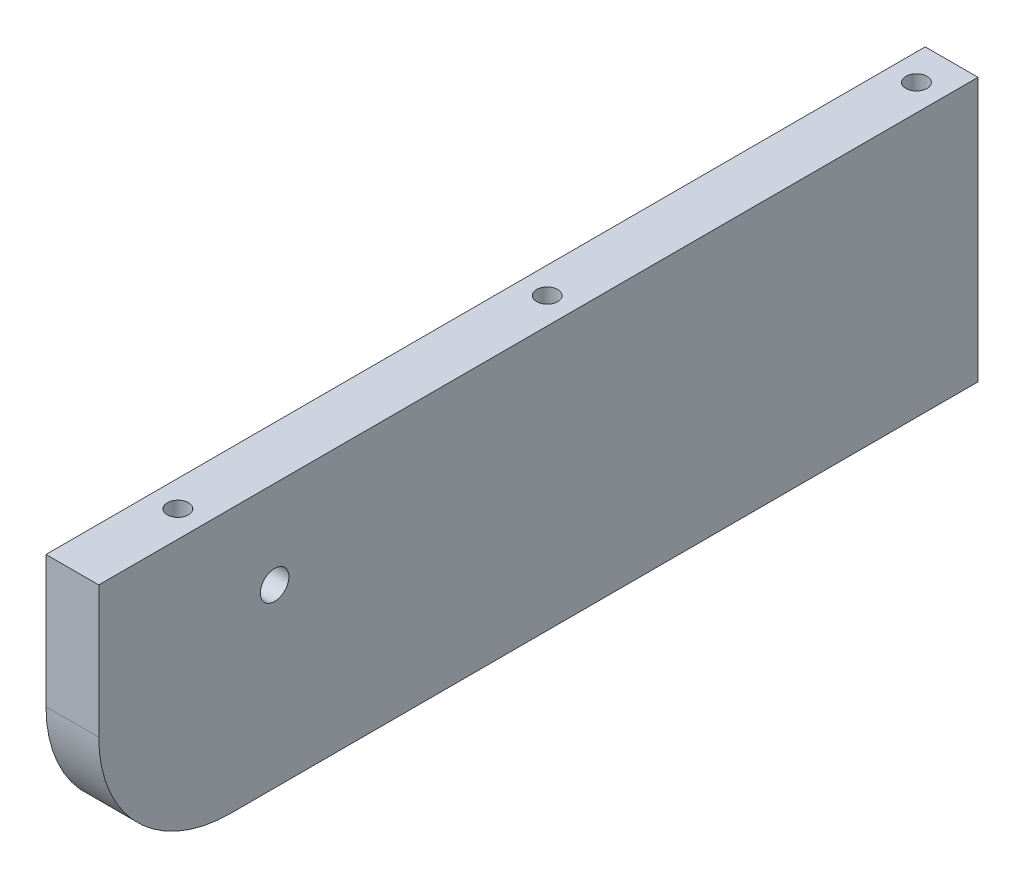
SolidWorks part; units mm, degrees
ref_plane "Front Plane" through (0, 0, 0) normal (0, 0, 1) x (1, 0, 0)
ref_plane "Top Plane" through (0, 0, 0) normal (0, 1, 0) x (1, 0, 0)
ref_plane "Right Plane" through (0, 0, 0) normal (1, 0, 0) x (0, 0, -1)
sketch "Sketch1" plane through (0, 0, 0) normal (1, 0, 0) x (0, 0, -1)
  line L1 (-50, -15) -> (50, -15)
  line L2 (-50, -15) -> (-50, 15)
  line L3 (-50, 15) -> (50, 15)
  line L4 (50, -15) -> (50, 15)
  line L5 (-50, -15) -> (50, 15) construction
  line L6 (-50, 15) -> (50, -15) construction
  circle A1 centre (-30, 5) radius 1.625
  point P0 (0, 0)
  dimension "D3" = 3.25
  dimension "D1" = 30
  dimension "D2" = 100
  dimension "D4" = 10
  dimension "D5" = 20
extrude "Boss-Extrude1" add sketch "Sketch1" along normal blind 6
fillet "Fillet1" radius 15 1 edges at (3, -15, 50)
hole_wizard "CBORE for M2 SHCS1" positions "Sketch2" profile "Sketch3" counterbore size "M2" standard "ANSI Metric"
sketch "Sketch2" plane through (-622.2935, 25, -1323.2827) normal (0, 1, 0) x (1, 0, 0)
  line L3 (625.2935, -1277.2827) -> (625.2935, -1361.2827) construction
  line L5 (727.2935, -1277.2827) -> (727.2935, -1361.2827) construction
  circle A0 centre (727.2935, -1277.2827) radius 2.243
  circle A1 centre (727.2935, -1361.2827) radius 2.2384
  circle A3 centre (625.2935, -1277.2827) radius 2.3325
  circle A4 centre (625.2935, -1361.2827) radius 1.7576
  circle A5 centre (625.2935, -1319.2827) radius 1.8624
  circle A6 centre (727.2935, -1319.2827) radius 2.0271
  point P1 (727.2935, -1277.2827)
  point P8 (727.2935, -1361.2827)
  point P15 (625.2935, -1277.2827)
  point P17 (625.2935, -1361.2827)
  point P19 (625.2935, -1319.2827)
  point P27 (727.2935, -1319.2827)
sketch "Sketch3" plane through (105, 25, -46) normal (1, 0, 0) x (0, 0, 1)
  line L0 (0, 0) -> (0, 20.721)
  line L1 (0, 20.721) -> (1.2, 20)
  line L2 (1.2, 20) -> (1.2, 2)
  line L3 (1.2, 2) -> (2.2, 2)
  line L4 (2.2, 2) -> (2.2, 0)
  line L5 (2.2, 0) -> (0, 0)
  line L6 (0, 20.721) -> (-1.2, 20) construction
  line L7 (0, -6.35) -> (0, 107.95) construction
  dimension "Hole Dia." = 2.4
  dimension "Hole Depth" = 20
  dimension "C'Bore Dia." = 4.4
  dimension "C'Bore Depth" = 2
  dimension "Drill Angle" = 118
